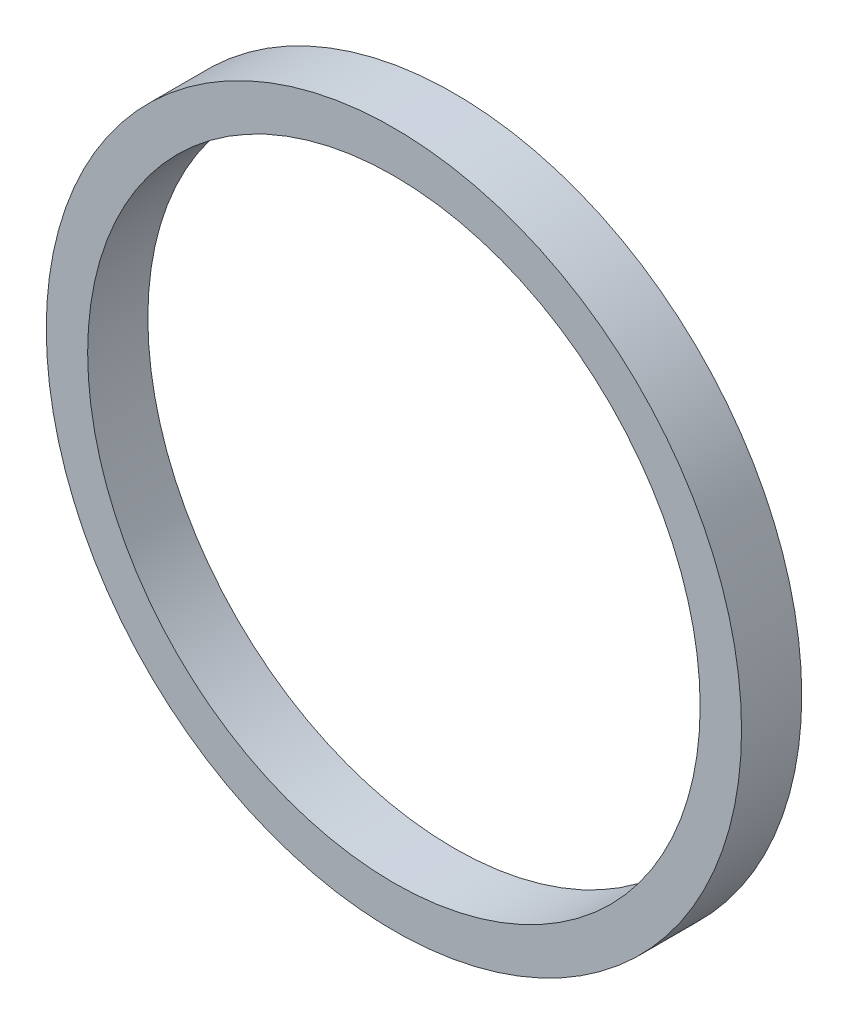
SolidWorks part; units mm, degrees
material "ABS"
ref_plane "Front Plane" through (0, 0, 0) normal (0, 0, 1) x (1, 0, 0)
ref_plane "Top Plane" through (0, 0, 0) normal (0, 1, 0) x (1, 0, 0)
ref_plane "Right Plane" through (0, 0, 0) normal (1, 0, 0) x (0, 0, -1)
sketch "Sketch1" plane through (0, 0, 0) normal (0, 0, 1) x (1, 0, 0)
  circle A0 centre (0, 0) radius 5.0875
  circle A1 centre (0, 0) radius 5.775
  dimension "D1" = 10.175
  dimension "D2" = 11.55
extrude "Boss-Extrude1" add sketch "Sketch1" along normal blind 1
equation "\"RingPinShaft\"= 5.05"
equation "\"CenterBearingOut\"=32.00"
equation "\"RingPostIn\"=5.15"
equation "\"CamBearingOut\"=15.1"
equation "\"DiskOutputShaft\"=10.1"
equation "\"CenterShaft\"=25.2"
equation "\"Eccentricity\"=2"
equation "\"CycCamShaft\"=10.05"
equation "\"D1@Sketch1\"=\"CycCamShaft\" + 0.125"
equation "\"D2@Sketch1\"=\"CycCamShaft\"+1.5"
